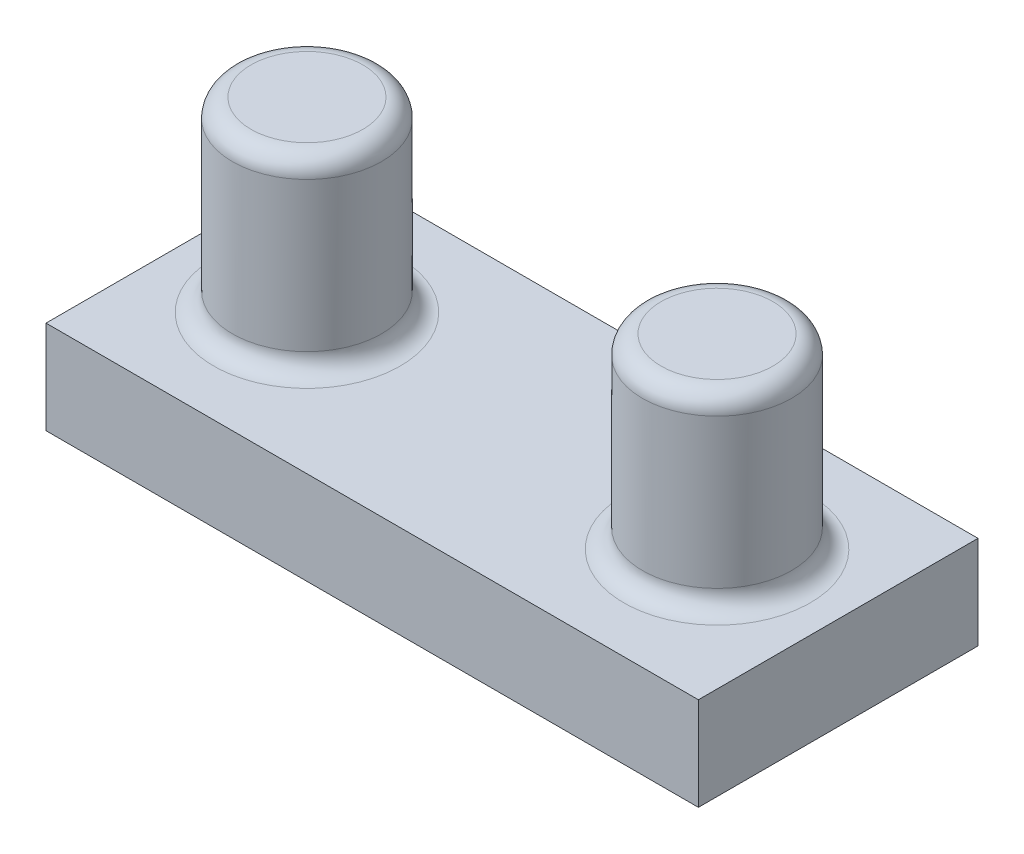
SolidWorks part; units mm, degrees
ref_plane "Front Plane" through (0, 0, 0) normal (0, 0, 1) x (1, 0, 0)
ref_plane "Top Plane" through (0, 0, 0) normal (0, 1, 0) x (1, 0, 0)
ref_plane "Right Plane" through (0, 0, 0) normal (1, 0, 0) x (0, 0, -1)
sketch "Sketch1" plane through (0, 0, 0) normal (0, 1, 0) x (1, 0, 0)
  line L0 (34.9998, 7.1697) -> (-26.696, 7.1697) construction
  circle A0 centre (11.0867, 7.1697) radius 4
  circle A1 centre (-10.9133, 7.1697) radius 4
  point P6 (0, 0)
  dimension "D1" = 22
  dimension "D2" = 8
  dimension "D3" = 8
extrude "Boss-Extrude1" add sketch "Sketch1" along normal blind 10
sketch "Sketch2" plane through (0, 0, 0) normal (0, -1, 0) x (-1, 0, 0)
  line L1 (17.4133, -0.3303) -> (-17.5867, -0.3303)
  line L2 (17.4133, -0.3303) -> (17.4133, 14.6697)
  line L3 (17.4133, 14.6697) -> (-17.5867, 14.6697)
  line L4 (-17.5867, -0.3303) -> (-17.5867, 14.6697)
  circle A0 centre (10.9133, 7.1697) radius 4 construction
  dimension "D1" = 35
  dimension "D2" = 6.5
  dimension "D3" = 15
  dimension "D4" = 7.5
extrude "Boss-Extrude2" add sketch "Sketch2" along normal blind 5
fillet "Fillet1" radius 1 4 edges at (-10.9133, 0, -11.1697) (11.0867, 0, -3.1697) (-10.9133, 10, -3.1697) (11.0867, 10, -3.1697)
sketch "Sketch3" plane through (0, 0, -14.6697) normal (0, 0, -1) x (-1, 0, 0)
  line L0 (15.3805, -4.4112) -> (-14.2204, -4.4112) construction
  text T0 "22 mm"
extrude "Cut-Extrude1" cut sketch "Sketch3" against normal blind 1
